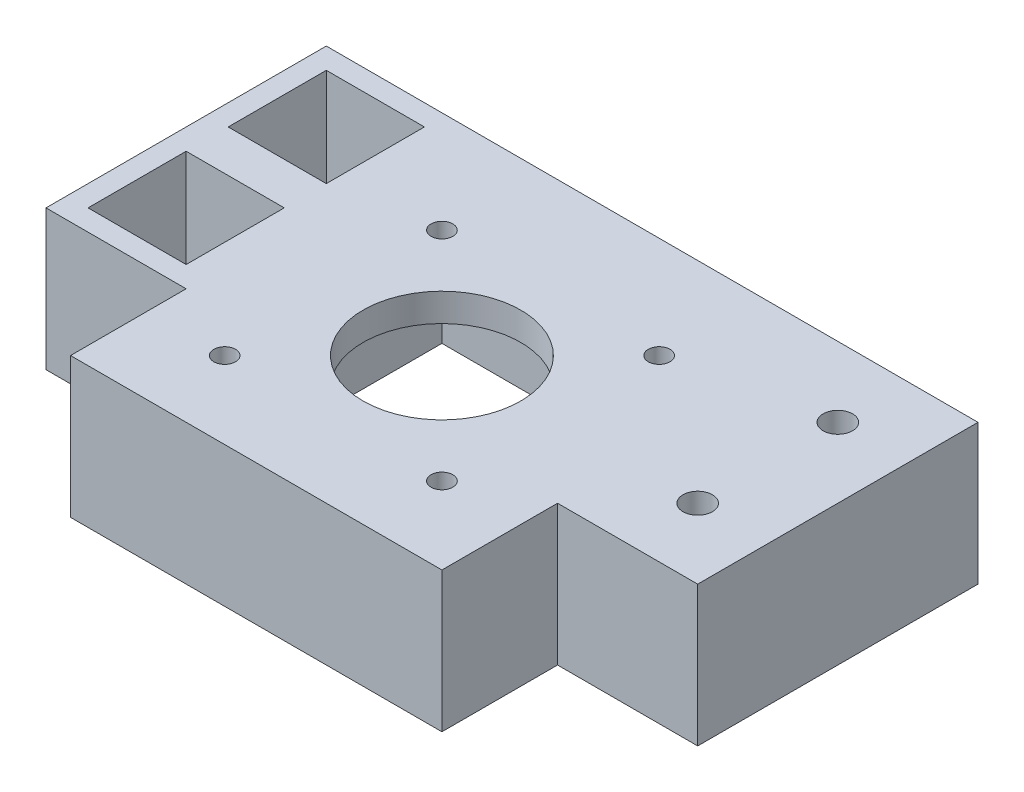
SolidWorks part; units mm, degrees
ref_plane "Front Plane" through (0, 0, 0) normal (0, 0, 1) x (1, 0, 0)
ref_plane "Top Plane" through (0, 0, 0) normal (0, 1, 0) x (1, 0, 0)
ref_plane "Right Plane" through (0, 0, 0) normal (1, 0, 0) x (0, 0, -1)
sketch "Sketch1" plane through (0, 0, 0) normal (0, 1, 0) x (1, 0, 0)
  line L0 (0, 0) -> (-15.5, 0)
  line L1 (-21.5, 0) -> (-21.5, 21.5)
  line L2 (-15.5, 0) -> (-15.5, 15.5)
  line L3 (-21.5, 21.5) -> (21.5, 21.5)
  line L4 (-21.5, 21.5) -> (-21.5, -21.5)
  line L5 (-21.5, -21.5) -> (21.5, -21.5)
  line L6 (21.5, 21.5) -> (21.5, -21.5)
  line L7 (-26.5, 26.5) -> (-26.5, -26.5)
  line L8 (-15.5, 15.5) -> (15.5, 15.5)
  line L9 (-15.5, 15.5) -> (-15.5, -15.5)
  line L10 (-15.5, -15.5) -> (15.5, -15.5)
  line L11 (15.5, 15.5) -> (15.5, -15.5)
  line L12 (-26.5, -26.5) -> (26.5, -26.5)
  line L13 (26.5, 26.5) -> (26.5, -26.5)
  line L14 (-26.5, 26.5) -> (26.5, 26.5)
  line L15 (0, 0) -> (80, 0)
  line L16 (80, 0) -> (60, 0)
  line L17 (60, 0) -> (40, 0)
  line L18 (80, 0) -> (90, 0)
  line L19 (90, 0) -> (90, 10)
  line L20 (90, 10) -> (26.5, 10)
  line L21 (90, 0) -> (90, -10)
  line L22 (90, -10) -> (26.5, -10)
  circle A0 centre (0, 0) radius 11.25
  circle A1 centre (-15.5, 15.5) radius 1.55
  circle A2 centre (15.5, 15.5) radius 1.55
  circle A3 centre (15.5, -15.5) radius 1.55
  circle A4 centre (-15.5, -15.5) radius 1.55
  circle A5 centre (80, 0) radius 2.1
  circle A6 centre (60, 0) radius 2.1
  circle A7 centre (40, 0) radius 2.1
  dimension "D1" = 5
sketch "Sketch2" plane through (0, 0, 0) normal (0, 1, 0) x (1, 0, 0)
  line L0 (0, 0) -> (80, 0) construction
  line L1 (-26.5, 26.5) -> (26.5, 26.5)
  line L2 (26.5, 26.5) -> (26.5, 10)
  line L3 (26.5, 10) -> (90, 10)
  line L4 (90, 10) -> (90, -10)
  line L5 (90, -10) -> (26.5, -10)
  line L6 (26.5, -10) -> (26.5, -26.5)
  line L7 (26.5, -26.5) -> (-26.5, -26.5)
  line L8 (-26.5, -26.5) -> (-26.5, 26.5)
  circle A0 centre (0, 0) radius 11.25
  circle A1 centre (-15.5, 15.5) radius 1.55
  circle A2 centre (15.5, 15.5) radius 1.55
  circle A3 centre (15.5, -15.5) radius 1.55
  circle A4 centre (-15.5, -15.5) radius 1.55
  circle A5 centre (40, 0) radius 2.1
  circle A6 centre (60, 0) radius 2.1
  circle A7 centre (80, 0) radius 2.1
extrude "Boss-Extrude1" add sketch "Sketch2" along normal blind 4
sketch "Sketch3" plane through (0, 0, 0) normal (0, 1, 0) x (1, 0, 0)
  line L0 (29.5, -7) -> (29.5, 7)
  line L1 (-26.5, -26.5) -> (26.5, -26.5)
  line L2 (-26.5, -26.5) -> (-26.5, 26.5)
  line L3 (-26.5, 26.5) -> (26.5, 26.5)
  line L4 (26.5, -26.5) -> (26.5, -10)
  line L5 (21.5, -21.5) -> (-21.5, -21.5)
  line L6 (21.5, -21.5) -> (21.5, 21.5)
  line L7 (21.5, 21.5) -> (-21.5, 21.5)
  line L8 (-21.5, -21.5) -> (-21.5, 21.5)
  line L9 (26.5, -10) -> (90, -10)
  line L11 (26.5, 10) -> (90, 10)
  line L12 (90, -10) -> (90, 10)
  line L13 (29.5, 7) -> (87, 7)
  line L14 (87, -7) -> (87, 7)
  line L15 (29.5, -7) -> (87, -7)
  line L16 (26.5, -10) -> (26.5, 10) construction
  line L17 (26.5, 10) -> (26.5, 26.5)
  dimension "D1" = 3
extrude "Boss-Extrude2" add sketch "Sketch3" against normal blind 10
sketch "Sketch4" plane through (0, 4, 0) normal (0, 1, 0) x (1, 0, 0)
  line L0 (26.5, 10) -> (26.5, 30)
  line L1 (26.5, 30) -> (90, 30)
  line L2 (90, 30) -> (90, 10)
  line L3 (90, 10) -> (26.5, 10)
  line L4 (80, 0) -> (80, 20)
  line L5 (60, 0) -> (60, 20)
  line L6 (40, 0) -> (40, 20)
  circle A0 centre (80, 20) radius 2.1
  circle A1 centre (60, 20) radius 2.1
  circle A2 centre (40, 20) radius 2.1
extrude "Boss-Extrude3" add sketch "Sketch4" against normal up to surface (4 mm away)
sketch "Sketch5" plane through (0, 0, 0) normal (0, -1, 0) x (1, 0, 0)
  line L1 (87, -13) -> (29.5, -13)
  line L2 (29.5, -13) -> (29.5, -26.5)
  line L3 (29.5, -26.5) -> (29.5, -27)
  line L4 (29.5, -27) -> (87, -27)
  line L5 (90, -10) -> (26.5, -10)
  line L6 (26.5, -10) -> (26.5, -26.5)
  line L7 (26.5, -26.5) -> (26.5, -30)
  line L8 (26.5, -30) -> (90, -30)
  line L9 (90, -30) -> (90, -10)
  line L10 (90, -10) -> (26.5, -10)
  line L11 (26.5, -10) -> (26.5, -26.5)
  line L12 (26.5, -26.5) -> (26.5, -30)
  line L13 (26.5, -30) -> (90, -30)
  line L14 (90, -30) -> (90, -10)
  line L15 (87, -27) -> (87, -13)
  dimension "D1" = 0
  dimension "D2" = 3
extrude "Boss-Extrude4" add sketch "Sketch5" along normal up to surface (10 mm away) up to face at (58.25, -10, 0)
sketch "Sketch6" plane through (0, -10, 0) normal (0, -1, 0) x (1, 0, 0)
  line L0 (60, 0) -> (80, 0)
  line L1 (26.5, -30) -> (90, -30) construction
  line L2 (90, 10) -> (70, 10)
  line L3 (90, 10) -> (90, -30)
  line L4 (90, -30) -> (70, -30)
  line L5 (70, 10) -> (70, -30)
extrude "Cut-Extrude1" cut sketch "Sketch6" against normal blind 31
sketch "Sketch7" plane through (0, 0, 0) normal (0, -1, 0) x (1, 0, 0)
  line L0 (26.5, -30) -> (70, -30) construction
  line L1 (70, 10) -> (67, 10)
  line L2 (70, 10) -> (70, -30)
  line L3 (70, -30) -> (67, -30)
  line L4 (67, 10) -> (67, -30)
extrude "Boss-Extrude5" add sketch "Sketch7" along normal up to surface (10 mm away) up to face at (36.9375, -10, -7.5)
sketch "Sketch8" plane through (0, -10, 0) normal (0, -1, 0) x (1, 0, 0)
  line L0 (60, -20) -> (40, -20)
  line L1 (26.5, -30) -> (70, -30) construction
  line L2 (50, -30) -> (70, -30)
  line L3 (50, -30) -> (50, 10)
  line L4 (50, 10) -> (70, 10)
  line L5 (70, -30) -> (70, 10)
extrude "Cut-Extrude2" cut sketch "Sketch8" against normal blind 31
sketch "Sketch9" plane through (0, 0, 0) normal (0, -1, 0) x (1, 0, 0)
  line L0 (29.5, 7) -> (50, 7) construction
  line L1 (50, -27) -> (47, -27)
  line L2 (50, -27) -> (50, 7)
  line L3 (50, 7) -> (47, 7)
  line L4 (47, -27) -> (47, 7)
extrude "Boss-Extrude6" add sketch "Sketch9" along normal up to surface (10 mm away) up to face at (0, -10, 0)
sketch "Sketch10" plane through (0, -10, 0) normal (0, -1, 0) x (1, 0, 0)
  line L0 (40, -20) -> (29.5, -20)
  line L1 (29.5, -13) -> (29.5, -27) construction
  line L2 (29.5, -20) -> (36.5, -20)
  line L3 (36.5, -20) -> (36.5, 0)
  circle A0 centre (36.5, -20) radius 2.1
  circle A1 centre (36.5, 0) radius 2.1
extrude "Cut-Extrude3" cut sketch "Sketch10" against normal blind 31
sketch "Sketch11" plane through (0, 0, 0) normal (0, -1, 0) x (1, 0, 0)
  circle A0 centre (36.5, -20) radius 2.1
  circle A1 centre (40, -20) radius 2.1
  circle A2 centre (40, 0) radius 2.1
  circle A3 centre (36.5, 0) radius 2.1
  arc M2 (38.25, -18.8392) -> (38.25, -21.1608) centre (40, -20) cw
extrude "Boss-Extrude7" add sketch "Sketch11" against normal up to surface (4 mm away) contours A0 M2 | A3 A2
sketch "Sketch12" plane through (0, -10, 0) normal (0, -1, 0) x (1, 0, 0)
  line L0 (36.5, -20) -> (43.5, -20)
  line L1 (43.5, -20) -> (46.5, -20)
  line L2 (46.5, -20) -> (46.5, -36.5241)
  line L4 (46.5, -36.5241) -> (58.006, -36.5241)
  line L5 (46.5, -36.5241) -> (46.5, 17.0682)
  line L6 (46.5, 17.0682) -> (58.006, 17.0682)
  line L7 (58.006, -36.5241) -> (58.006, 17.0682)
  line M1 (47, 7) -> (47, -7)
  line M2 (47, -7) -> (29.5, -7)
  line M4 (29.5, 7) -> (47, 7)
  line M5 (29.5, -13) -> (47, -13)
  line M6 (47, -13) -> (47, -27)
  line M7 (47, -27) -> (29.5, -27)
  line M9 (26.5, -30) -> (50, -30)
  line M10 (50, -30) -> (50, 10)
  line M11 (50, 10) -> (26.5, 10)
extrude "Cut-Extrude4" cut sketch "Sketch12" against normal blind 31 contours L4 L7 L6 L5 L2 M11 M10 M9 | L5 L2 M5 M6 M7 M9 M10 M11 M4 M1 M2 | L5 L2 M7 M6 M5 | L5 M2 M1 M4
sketch "Sketch13" plane through (0, 0, 0) normal (0, -1, 0) x (1, 0, 0)
  line L0 (29.5, 7) -> (46.5, 7) construction
  line L1 (46.5, -27) -> (43.5, -27)
  line L2 (46.5, -27) -> (46.5, 7)
  line L3 (46.5, 7) -> (43.5, 7)
  line L4 (43.5, -27) -> (43.5, 7)
extrude "Boss-Extrude8" add sketch "Sketch13" along normal up to surface (10 mm away) up to face at (0, -10, 0)
sketch "Sketch15" plane through (0, 4, 0) normal (0, 1, 0) x (1, 0, 0)
  line L0 (26.5, -10) -> (-26.5, -10)
  line L1 (-46.5, 30) -> (-26.5, 30)
  line L2 (-46.5, 30) -> (-46.5, -10)
  line L3 (-46.5, -10) -> (-26.5, -10)
  line L4 (-26.5, 30) -> (-26.5, -10)
  line L5 (-26.5, 26.5) -> (-26.5, -26.5) construction
  circle A0 centre (-36.5, 20) radius 2.1
  circle A1 centre (-36.5, 0) radius 2.1
  line M16 (-26.5, 26.5) -> (-26.5, -26.5)
extrude "Boss-Extrude9" add sketch "Sketch15" against normal up to surface (4 mm away) contours L4 L1 L2 L3 A1 A0 M16 up to face at (36.5, 0, -22.1)
sketch "Sketch16" plane through (0, 0, 0) normal (0, -1, 0) x (1, 0, 0)
  line L0 (-29.5, -27) -> (-29.5, 7)
  line L1 (-26.5, -30) -> (-46.5, -30)
  line L2 (-26.5, -30) -> (-26.5, 10)
  line L3 (-26.5, 10) -> (-46.5, 10)
  line L4 (-46.5, -30) -> (-46.5, 10)
  line L5 (-29.5, 7) -> (-43.5, 7)
  line L6 (-43.5, -27) -> (-43.5, 7)
  line L7 (-29.5, -27) -> (-43.5, -27)
  line L8 (-29.5, -10) -> (-43.5, -10)
  line L9 (-29.5, -7) -> (-43.5, -7)
  line L10 (-29.5, -13) -> (-43.5, -13)
  line M10 (-46.5, -30) -> (-26.5, -30)
  line M11 (-26.5, -30) -> (-26.5, -26.5)
  line M12 (-26.5, -26.5) -> (-26.5, 10)
  line M13 (-26.5, 10) -> (-46.5, 10)
  line M14 (-46.5, 10) -> (-46.5, -30)
  dimension "D1" = 3
  dimension "D2" = 3
  dimension "D3" = 3
extrude "Boss-Extrude10" add sketch "Sketch16" along normal up to surface (10 mm away) contours L0 L7 L6 L5 M14 M10 M11 M12 M13 | L10 L0 L8 L6 | L0 L9 L6 L8
sketch "Sketch17" plane through (0, -10, 0) normal (0, -1, 0) x (1, 0, 0)
  line L0 (26.5, -26.5) -> (-26.5, -26.5) construction
  line L1 (26.5, -30) -> (-26.5, -30)
  line L2 (26.5, -30) -> (26.5, -26.5)
  line L3 (26.5, -26.5) -> (-26.5, -26.5)
  line L4 (-26.5, -30) -> (-26.5, -26.5)
extrude "Boss-Extrude11" add sketch "Sketch17" against normal up to surface (14 mm away)
ref_plane "Plane1" through (46.5, -10, -30) normal (1, 0, 0) x (0, 0, -1)
sketch "Sketch19" plane through (0, -10, 0) normal (0, -1, 0) x (1, 0, 0)
  line L4 (21.5, -21.5) -> (21.5, 21.5)
  line L5 (-21.5, -21.5) -> (21.5, -21.5)
  line L6 (-21.5, 21.5) -> (-21.5, -21.5)
  line L7 (21.5, 21.5) -> (-21.5, 21.5)
  line L8 (21.5, -21.5) -> (21.5, 21.5)
  line L9 (-21.5, -21.5) -> (21.5, -21.5)
  line L10 (-21.5, 21.5) -> (-21.5, -21.5)
  line L11 (21.5, 21.5) -> (-21.5, 21.5)
  line L12 (43.5, -13) -> (29.5, -13)
  line L13 (43.5, -27) -> (43.5, -13)
  line L14 (29.5, -27) -> (43.5, -27)
  line L15 (29.5, -13) -> (29.5, -27)
  line L16 (43.5, -13) -> (29.5, -13)
  line L17 (43.5, -27) -> (43.5, -13)
  line L18 (29.5, -27) -> (43.5, -27)
  line L19 (29.5, -13) -> (29.5, -27)
  line L20 (43.5, -7) -> (43.5, 7)
  line L21 (29.5, -7) -> (43.5, -7)
  line L22 (29.5, 7) -> (29.5, -7)
  line L23 (43.5, 7) -> (29.5, 7)
  line L24 (43.5, -7) -> (43.5, 7)
  line L25 (29.5, -7) -> (43.5, -7)
  line L26 (29.5, 7) -> (29.5, -7)
  line L27 (43.5, 7) -> (29.5, 7)
  line L28 (-29.5, -27) -> (-29.5, -13)
  line L29 (-43.5, -27) -> (-29.5, -27)
  line L30 (-43.5, -13) -> (-43.5, -27)
  line L31 (-29.5, -13) -> (-43.5, -13)
  line L32 (-29.5, -27) -> (-29.5, -13)
  line L33 (-43.5, -27) -> (-29.5, -27)
  line L34 (-43.5, -13) -> (-43.5, -27)
  line L35 (-29.5, -13) -> (-43.5, -13)
  line L36 (-29.5, -7) -> (-29.5, 7)
  line L37 (-43.5, -7) -> (-29.5, -7)
  line L38 (-43.5, 7) -> (-43.5, -7)
  line L39 (-29.5, 7) -> (-43.5, 7)
  line L40 (-29.5, -7) -> (-29.5, 7)
  line L41 (-43.5, -7) -> (-29.5, -7)
  line L42 (-43.5, 7) -> (-43.5, -7)
  line L43 (-29.5, 7) -> (-43.5, 7)
  line L48 (-46.5, 10) -> (-46.5, -30)
  line L49 (-46.5, -30) -> (46.5, -30)
  line L50 (46.5, -30) -> (46.5, 10)
  line L51 (46.5, 10) -> (26.5, 10)
  line L52 (26.5, 10) -> (26.5, 26.5)
  line L53 (26.5, 26.5) -> (-26.5, 26.5)
  line L54 (-26.5, 26.5) -> (-26.5, 10)
  line L55 (-26.5, 10) -> (-46.5, 10)
  line L56 (-46.5, 10) -> (-46.5, -30)
  line L57 (-46.5, -30) -> (46.5, -30)
  line L58 (46.5, -30) -> (46.5, 10)
  line L59 (46.5, 10) -> (26.5, 10)
  line L60 (26.5, 10) -> (26.5, 26.5)
  line L61 (26.5, 26.5) -> (-26.5, 26.5)
  line L62 (-26.5, 26.5) -> (-26.5, 10)
  line L63 (-26.5, 10) -> (-46.5, 10)
  dimension "D1" = 0
  dimension "D2" = 0
  dimension "D3" = 0
  dimension "D4" = 0
  dimension "D5" = 0
  dimension "D6" = 0
extrude "Boss-Extrude12" add sketch "Sketch19" along normal blind 6
sketch "Sketch20" plane through (0, 0, 0) normal (0, -1, 0) x (1, 0, 0)
  line L1 (-43.5, -27) -> (-29.5, -27)
  line L2 (-43.5, -27) -> (-43.5, -13)
  line L3 (-43.5, -13) -> (-29.5, -13)
  line L4 (-29.5, -27) -> (-29.5, -13)
  line L5 (-29.5, 7) -> (-43.5, 7)
  line L6 (-29.5, 7) -> (-29.5, -7)
  line L7 (-29.5, -7) -> (-43.5, -7)
  line L8 (-43.5, 7) -> (-43.5, -7)
extrude "Cut-Extrude5" cut sketch "Sketch20" against normal blind 6
sketch "Sketch21" plane through (0, -16, 0) normal (0, -1, 0) x (1, 0, 0)
  line L1 (-43.5, -27) -> (-29.5, -27)
  line L2 (-43.5, -27) -> (-43.5, -13)
  line L3 (-43.5, -13) -> (-29.5, -13)
  line L4 (-29.5, -27) -> (-29.5, -13)
  line L5 (-29.5, -7) -> (-43.5, -7)
  line L6 (-29.5, -7) -> (-29.5, 7)
  line L7 (-29.5, 7) -> (-43.5, 7)
  line L8 (-43.5, -7) -> (-43.5, 7)
  circle A0 centre (-36.5, -20) radius 2.1
  circle A1 centre (-36.5, 0) radius 2.6
extrude "Boss-Extrude13" add sketch "Sketch21" against normal blind 4
